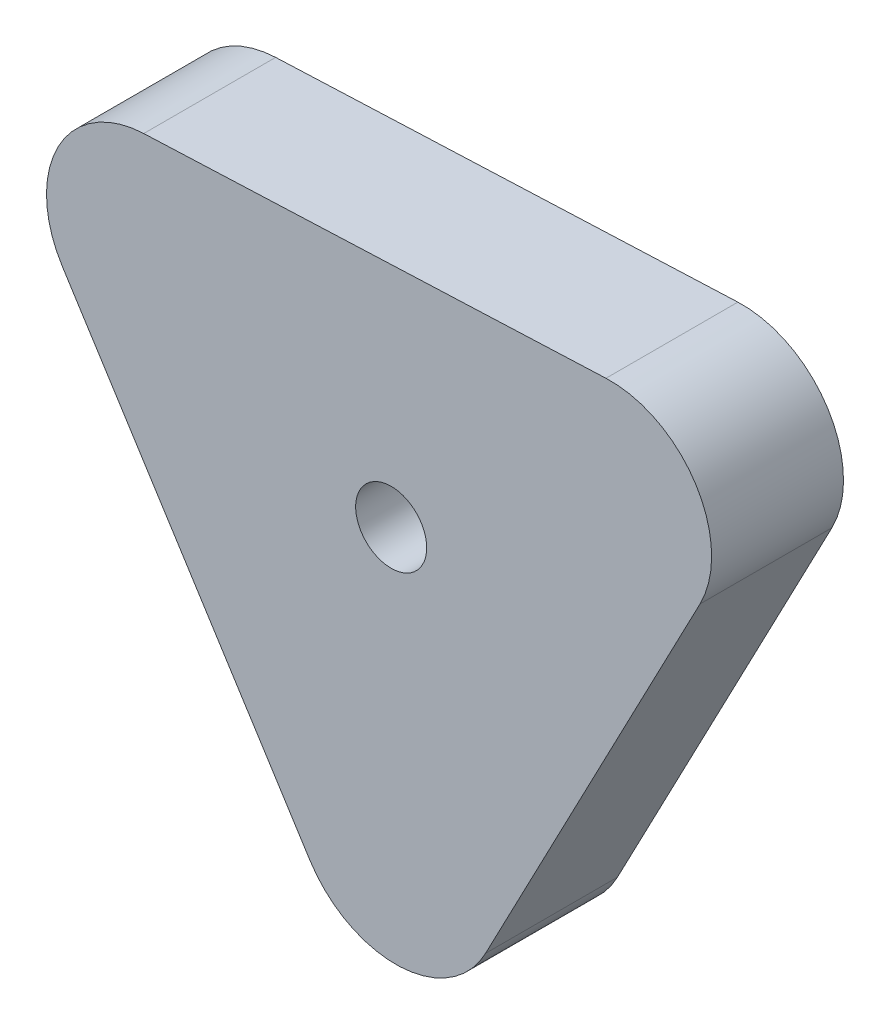
SolidWorks part; units mm, degrees
ref_plane "前视基准面" through (0, 0, 0) normal (0, 0, 1) x (1, 0, 0)
ref_plane "上视基准面" through (0, 0, 0) normal (0, 1, 0) x (1, 0, 0)
ref_plane "右视基准面" through (0, 0, 0) normal (1, 0, 0) x (0, 0, -1)
sketch "草图1" plane through (0, 0, 0) normal (0, 0, 1) x (1, 0, 0)
  line L1 (8.3558, -13.3364) -> (29.5019, 27.0671)
  line L2 (20.2279, 41.6955) -> (-25.3356, 39.8069)
  line L3 (-33.3672, 24.4611) -> (-8.9498, -14.0537)
  circle A0 centre (-1.5945, 17.6068) radius 46.3287 construction
  arc A1 (8.3558, -13.3364) -> (-8.9498, -14.0537) centre (-0.5041, -8.6993) cw
  arc A2 (-25.3356, 39.8069) -> (-33.3672, 24.4611) centre (-24.9215, 29.8155) ccw
  arc A3 (29.5019, 27.0671) -> (20.2279, 41.6955) centre (20.642, 31.7041) ccw
  circle A4 centre (-1.5945, 17.6068) radius 3.5
  point P10 (-42.6413, 39.0896)
  dimension "D1" = 10
extrude "凸台-拉伸2" add sketch "草图1" along normal blind 13 contours L2 A2 L3 A1 L1 A3
sketch "草图5" plane through (0, 0, 13) normal (0, 0, 1) x (1, 0, 0)
  circle A0 centre (-0.945, 18.3859) radius 3.5
extrude "切除-拉伸3" cut sketch "草图5" against normal blind 13
